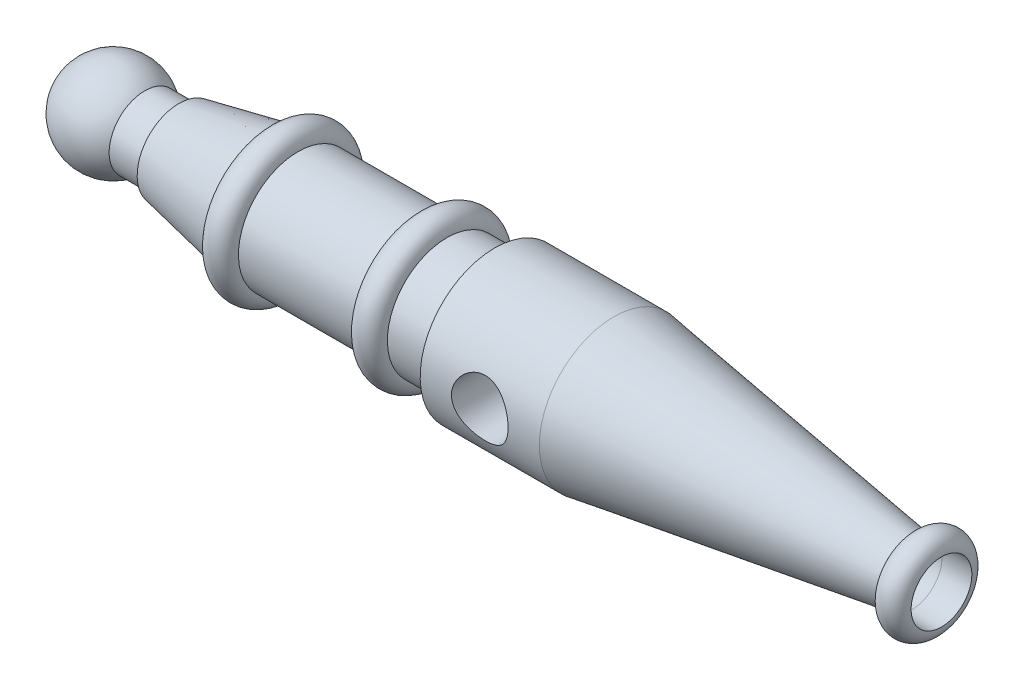
SolidWorks part; units mm, degrees
ref_plane "Plano frontal" through (0, 0, 0) normal (0, 0, 1) x (1, 0, 0)
ref_plane "Plano superior" through (0, 0, 0) normal (0, 1, 0) x (1, 0, 0)
ref_plane "Plano direito" through (0, 0, 0) normal (1, 0, 0) x (0, 0, -1)
sketch "Esboço1" plane through (0, 0, 0) normal (0, 0, 1) x (1, 0, 0)
  line L0 (5.2915, 6) -> (11, 6)
  line L2 (11, 6) -> (11, 7)
  line L3 (11, 7) -> (26, 10)
  line L5 (26, 0) -> (11, 0)
  line L7 (26, 0) -> (31, 0)
  line L8 (31, 10) -> (51, 10)
  line L10 (51, 0) -> (31, 0)
  line L12 (56, 0) -> (51, 0)
  line L13 (56, 10) -> (64, 10)
  line L15 (64, 0) -> (56, 0)
  line L17 (64, 12.5) -> (64, 10)
  line L19 (64.0034, 12.5) -> (64, 12.5)
  line L20 (64, 12.5) -> (84, 12.5)
  line L22 (84, 0) -> (64, 0)
  line L23 (84, 12.5) -> (134, 5.0963)
  line L24 (84, 0) -> (139, 0)
  line L25 (139, 0) -> (139, 5.0963)
  line L26 (-8, 0) -> (11, 0)
  line L28 (5.2915, 0) -> (11, 0)
  arc A0 (5.2915, 6) -> (-8, 0) centre (0, 0) ccw
  arc A1 (26, 10) -> (31, 10) centre (28.5, 10) cw
  arc A2 (51, 10) -> (56, 10) centre (53.5, 10) cw
  arc A3 (134, 5.0963) -> (139, 5.0963) centre (136.5, 5.0963) cw
  point P1 (53.5, 12.5)
  point P29 (74, 0)
  point P46 (53.5, 0)
  dimension "D1" = 16
  dimension "D5" = 2.5
  dimension "D6" = 53.5
  dimension "D8" = 2.5
  dimension "D9" = 8
  dimension "D12" = 74
  dimension "D14" = 2.5
  dimension "D15" = 6
  dimension "D2" = 11
  dimension "D3" = 28.5
  dimension "D4" = 15
  dimension "D7" = 20
  dimension "D10" = 20
  dimension "D13" = 55
  dimension "D16" = 139
  dimension "D17" = 5
  dimension "D18" = 5
  dimension "D19" = 12.5
  dimension "D20" = 7
  dimension "D21" = 10
  dimension "D22" = 12.5
  dimension "D23" = 10
revolve "Revolução2" add sketch "Esboço1" angle 360 about L22
sketch "Esboço2" plane through (0, 0, 0) normal (0, 0, 1) x (1, 0, 0)
  line L1 (84, 0) -> (64, 0) construction
  circle A0 centre (74, 0) radius 4.75
  dimension "D1" = 9.5
extrude "Corte-extrusão1" cut sketch "Esboço2" against normal through all both and the other way through all contours A0
sketch "Esboço3" plane through (139, 0, 0) normal (1, 0, 0) x (0, 0, -1)
  circle A0 centre (0, 0) radius 5.0963
extrude "Corte-extrusão2" cut sketch "Esboço3" against normal blind 50
